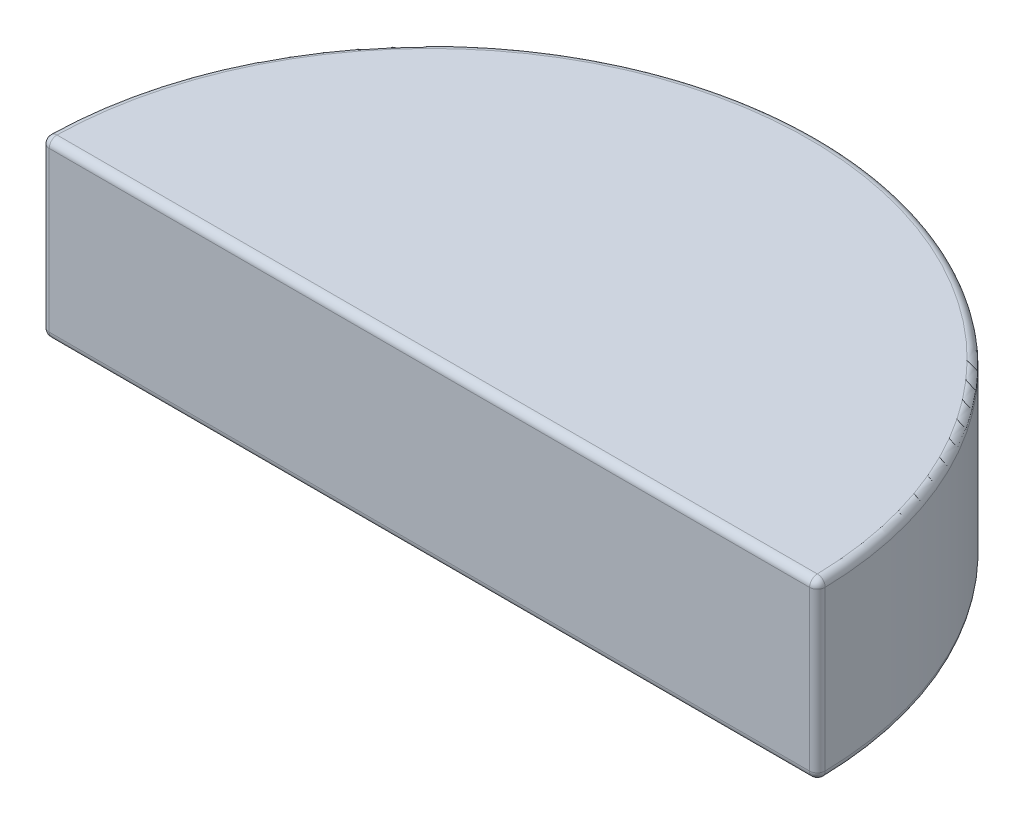
SolidWorks part; units mm, degrees
ref_plane "Front Plane" through (0, 0, 0) normal (0, 0, 1) x (1, 0, 0)
ref_plane "Top Plane" through (0, 0, 0) normal (0, 1, 0) x (1, 0, 0)
ref_plane "Right Plane" through (0, 0, 0) normal (1, 0, 0) x (0, 0, -1)
sketch "Sketch1" plane through (0, 0, 0) normal (0, 1, 0) x (1, 0, 0)
  line L0 (0, 0) -> (1000, 0)
  arc A0 (1000, 0) -> (0, 0) centre (500, 0) ccw
  dimension "D1" = 500
extrude "Boss-Extrude1" add sketch "Sketch1" along normal blind 225
fillet "Fillet1" radius 10 6 edges at (1000, 112.5, 0) (0, 112.5, 0) (500, 0, 0) (500, 0, -500) (500, 225, 0) (500, 225, -500)
